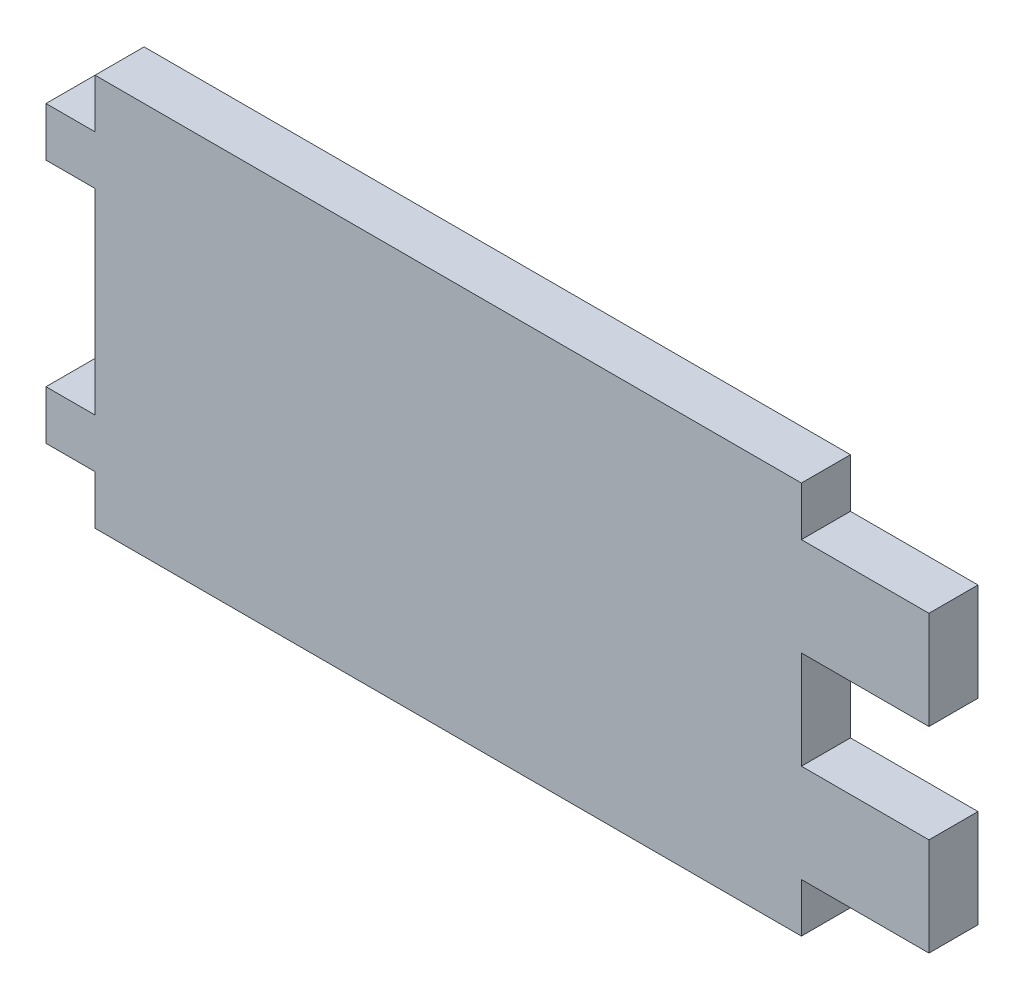
SolidWorks part; units mm, degrees
ref_plane "Plan de face" through (0, 0, 0) normal (0, 0, 1) x (1, 0, 0)
ref_plane "Plan de dessus" through (0, 0, 0) normal (0, 1, 0) x (1, 0, 0)
ref_plane "Plan de droite" through (0, 0, 0) normal (1, 0, 0) x (0, 0, -1)
sketch "Esquisse1" plane through (0, 0, 0) normal (0, 0, 1) x (1, 0, 0)
  line L1 (0, 0) -> (72, 0)
  line L2 (0, 0) -> (0, 5)
  line L3 (0, 40) -> (72, 40)
  line L4 (72, 0) -> (72, 5)
  line L5 (0, 35) -> (-5, 35)
  line L6 (0, 10) -> (0, 30)
  line L7 (0, 30) -> (-5, 30)
  line L8 (-5, 35) -> (-5, 30)
  line L9 (0, 5) -> (-5, 5)
  line L10 (72, 15) -> (85, 15)
  line L11 (0, 10) -> (-5, 10)
  line L12 (-5, 5) -> (-5, 10)
  line L13 (0, 35) -> (0, 40)
  line L14 (85, 5) -> (85, 15)
  line L15 (72, 5) -> (85, 5)
  line L16 (85, 35) -> (85, 25)
  line L17 (72, 25) -> (85, 25)
  line L18 (72, 35) -> (85, 35)
  line L19 (72, 35) -> (72, 40)
  line L20 (72, 15) -> (72, 25)
  dimension "D1" = 40
  dimension "D2" = 72
  dimension "D3" = 5
  dimension "D4" = 5
  dimension "D5" = 5
  dimension "D6" = 5
  dimension "D7" = 10
  dimension "D8" = 5
  dimension "D9" = 5
  dimension "D10" = 85
extrude "Boss.-Extru.1" add sketch "Esquisse1" along normal blind 5
